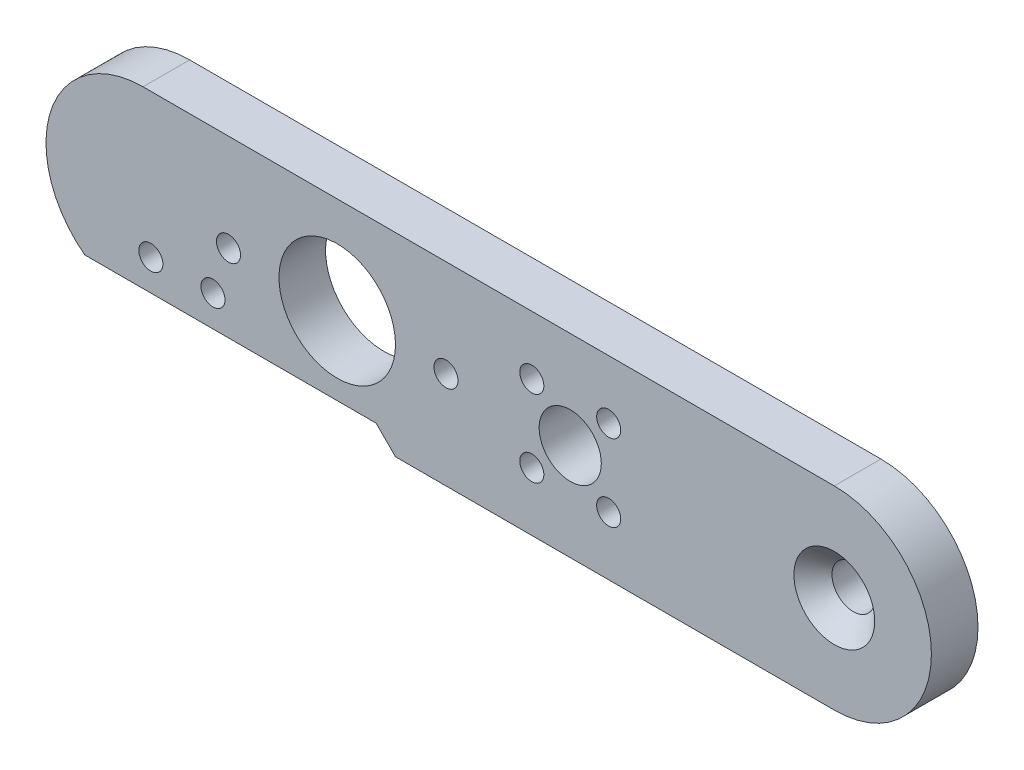
SolidWorks part; units mm, degrees
ref_plane "Front Plane" through (0, 0, 0) normal (0, 0, 1) x (1, 0, 0)
ref_plane "Top Plane" through (0, 0, 0) normal (0, 1, 0) x (1, 0, 0)
ref_plane "Right Plane" through (0, 0, 0) normal (1, 0, 0) x (0, 0, -1)
sketch "Sketch1" plane through (0, 0, 0) normal (0, 0, 1) x (1, 0, 0)
  line L0 (-44.5, 0) -> (44.5, 0) construction
  line L1 (-44.5, 12.5) -> (44.5, 12.5)
  line L2 (-12, -12.5) -> (44.5, -12.5)
  line L3 (10.5, 0) -> (10.5, 7) construction
  line L4 (10.5, 0) -> (15.4497, 4.9497) construction
  line L5 (3.5, 0) -> (17.5, 0) construction
  line L6 (10.5, 0) -> (5.5503, -4.9497) construction
  line L7 (5.5503, 4.9497) -> (15.4497, -4.9497) construction
  line L8 (-52, -10) -> (-14.5, -10)
  line L9 (-14.5, -10) -> (-12, -12.5)
  arc A0 (-44.5, 12.5) -> (-52, -10) centre (-44.5, 0) ccw
  arc A1 (44.5, -12.5) -> (44.5, 12.5) centre (44.5, 0) ccw
  circle A2 centre (10.5, 0) radius 4
  circle A3 centre (10.5, 0) radius 7 construction
  circle A4 centre (15.4497, 4.9497) radius 1.55
  circle A5 centre (5.5503, 4.9497) radius 1.55
  circle A6 centre (5.5503, -4.9497) radius 1.55
  circle A7 centre (15.4497, -4.9497) radius 1.55
  circle A8 centre (-33.5, 0) radius 1.55
  circle A9 centre (-19.5, 0) radius 7.5
  circle A10 centre (-5.5, 0) radius 1.55
  point P2 (0, 0)
  point P30 (-13.5935, -10)
  point P31 (0, 0)
  point P32 (0, 0)
  dimension "D2" = 12.5
  dimension "D3" = 8
  dimension "D5" = 14
  dimension "D7" = 3.1
  dimension "D9" = 3.1
  dimension "D10" = 3.1
  dimension "D14" = 15
  dimension "D15" = 3.1
  dimension "D16" = 3.1
  dimension "D1" = 89
  dimension "D4" = 34
  dimension "D6" = 45
  dimension "D8" = 45
  dimension "D11" = 45
  dimension "D12" = 22.5
  dimension "D13" = 44.5
  dimension "D17" = 30
  dimension "D18" = 14
  dimension "D19" = 14
  dimension "D20" = 59
extrude "Boss-Extrude1" add sketch "Sketch1" along normal blind 6
hole_wizard "CSK for M5 Flat Head Machine Screw1" positions "Sketch2" profile "Sketch3" countersink size "M5" standard "ANSI Metric" end condition through all
sketch "Sketch2" plane through (0, 0, 6) normal (0, 0, 1) x (1, 0, 0)
  point P0 (44.5, 0)
sketch "Sketch3" plane through (44.5, 0, 6) normal (1, 0, 0) x (0, -1, 0)
  line L0 (0, 0) -> (0, 6)
  line L1 (0, 6) -> (2.75, 6)
  line L2 (2.75, 6) -> (2.75, 2.45)
  line L3 (2.75, 2.45) -> (5.2, 0)
  line L5 (5.2, 0) -> (0, 0)
  line L6 (-2.75, 2.45) -> (-5.2, 0) construction
  line L11 (0, -6.35) -> (0, 107.95) construction
  dimension "Thru Hole Dia." = 5.5
  dimension "Thru Hole Depth" = 6
  dimension "Near C'Sink Dia." = 10.4
  dimension "Near C'Sink Angle" = 90
sketch "Sketch4" plane through (0, 0, 6) normal (0, 0, 1) x (1, 0, 0)
  line L0 (-46.3908, -6) -> (-27.3437, -6) construction
  line L1 (44.5, 12.5) -> (-44.5, 12.5) construction
  circle A0 centre (-43.5, -6) radius 1.55
  circle A1 centre (-35.5, -6) radius 1.55
  circle A2 centre (-19.5, 0) radius 7.5 construction
  circle A3 centre (-19.5, 0) radius 7.5
  dimension "D2" = 3.1
  dimension "D1" = 18.5
  dimension "D3" = 16
  dimension "D4" = 8
extrude "Cut-Extrude1" cut sketch "Sketch4" against normal through all
sketch "Sketch5" plane through (0, 0, 6) normal (0, 0, 1) x (1, 0, 0)
  circle A0 centre (-43.5, -6) radius 1.55 construction
  circle A1 centre (-35.5, -6) radius 1.55 construction
  circle A2 centre (-43.5, -6) radius 1.55
  circle A3 centre (-35.5, -6) radius 1.55
  circle A4 centre (-35.5, -6) radius 3
  circle A5 centre (-43.5, -6) radius 3
  dimension "D1" = 6
  dimension "D2" = 6
sketch "Sketch6" plane through (0, 0, 0) normal (0, 0, -1) x (-1, 0, 0)
  circle A0 centre (43.5, -6) radius 3 construction
  circle A1 centre (35.5, -6) radius 3 construction
  circle A2 centre (43.5, -6) radius 3
  circle A3 centre (35.5, -6) radius 3
extrude "Cut-Extrude3" cut sketch "Sketch6" against normal blind 3
